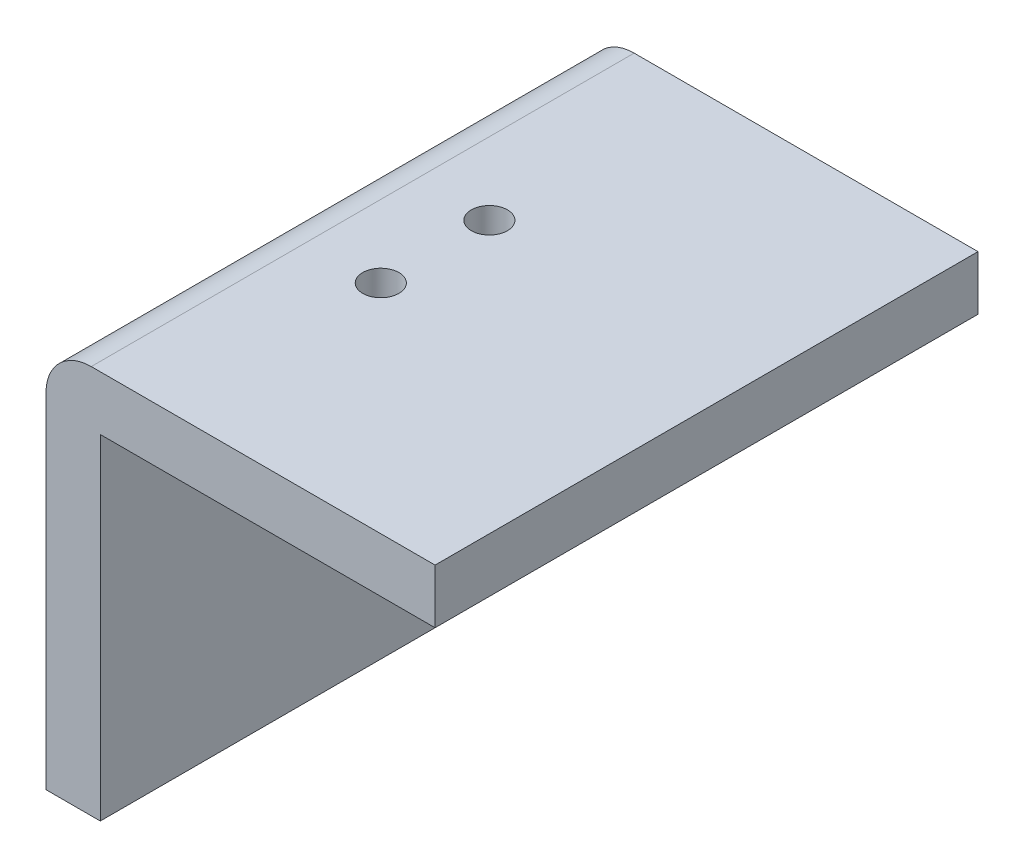
SolidWorks part; units mm, degrees
material "Acrilico TEC"
ref_plane "Front Plane" through (0, 0, 0) normal (0, 0, 1) x (1, 0, 0)
ref_plane "Top Plane" through (0, 0, 0) normal (0, 1, 0) x (1, 0, 0)
ref_plane "Right Plane" through (0, 0, 0) normal (1, 0, 0) x (0, 0, -1)
sketch "Sketch1" plane through (0, 0, 0) normal (0, 0, 1) x (1, 0, 0)
  line L0 (0, 0) -> (0, 19)
  line L1 (1, 20) -> (20, 20)
  line L2 (1.5, 0) -> (1.5, 18.5)
  line L3 (1.5, 18.5) -> (20, 18.5)
  line L4 (-1.5, 0) -> (-1.5, 19)
  line L5 (1, 21.5) -> (20, 21.5)
  line L6 (20, 21.5) -> (20, 18.5)
  line L7 (-1.5, 0) -> (1.5, 0)
  arc A0 (0, 19) -> (1, 20) centre (1, 19) cw
  arc A1 (1.5, 18.5) -> (1.5, 18.5) centre (1.5, 18.5) cw
  arc A2 (-1.5, 19) -> (1, 21.5) centre (1, 19) cw
  point P6 (0, 20)
  dimension "D3" = 1
  dimension "D1" = 20
  dimension "D2" = 20
  dimension "D4" = 1.5
  dimension "D5" = 1.5
extrude "Boss-Extrude1" add sketch "Sketch1" along normal blind 30 contours A0 L0 L7 L2 L3 L6 L1 | A2 L4 L7 L0 A0 L1 L6 L5
hole_wizard "Ø2.0mm Clearance Dowel Hole1" positions "Sketch2" profile "Sketch3" hole size "Ø2.0" standard "ISO" end condition through all
sketch "Sketch2" plane through (-21.9294, 18.5, -58.5) normal (0, -1, 0) x (-1, 0, 0)
  point P0 (-26.9294, -76.5)
  point P1 (-26.9294, -70.5)
sketch "Sketch3" plane through (5, 18.5, 18) normal (1, 0, 0) x (0, 0, -1)
  line L0 (0, 0) -> (0, 3)
  line L1 (0, 3) -> (1, 3)
  line L2 (1, 3) -> (1, 0)
  line L3 (1, 0) -> (0, 0)
  line L4 (0, -6.35) -> (0, 107.95) construction
  dimension "Thru Hole Dia." = 2
  dimension "Thru Hole Depth" = 3
